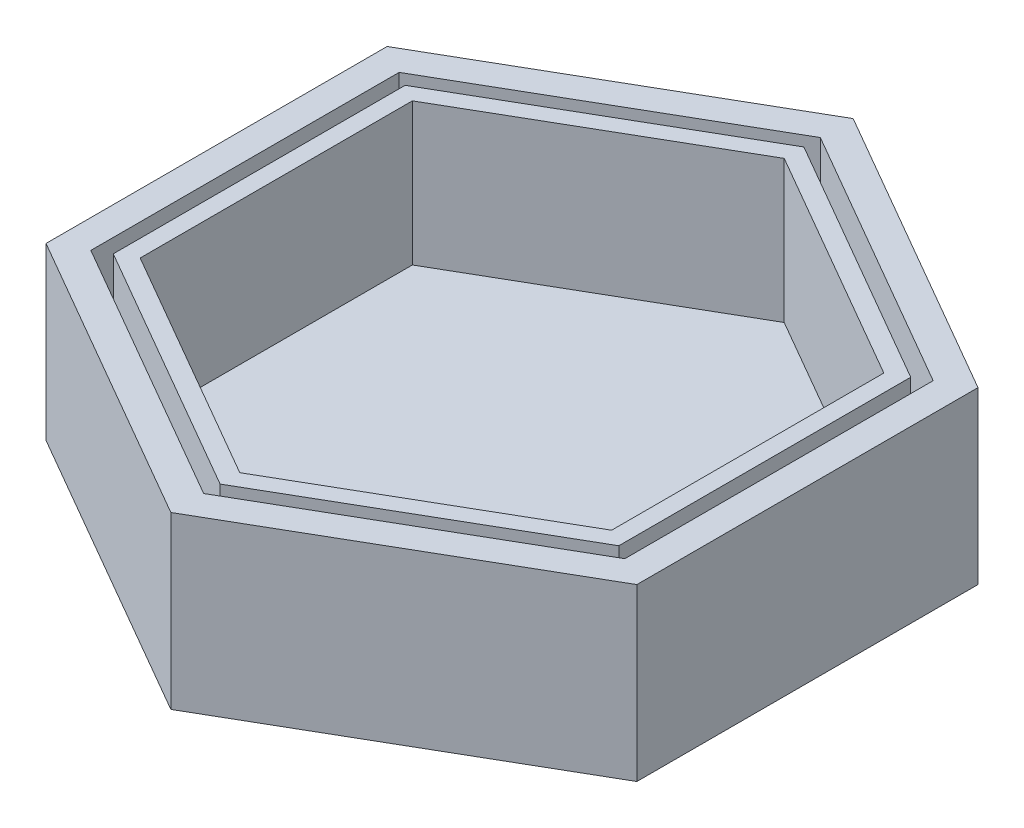
SolidWorks part; units mm, degrees
ref_plane "Front Plane" through (0, 0, 0) normal (0, 0, 1) x (1, 0, 0)
ref_plane "Top Plane" through (0, 0, 0) normal (0, 1, 0) x (1, 0, 0)
ref_plane "Right Plane" through (0, 0, 0) normal (1, 0, 0) x (0, 0, -1)
sketch "layout" plane through (0, 0, 0) normal (0, 1, 0) x (1, 0, 0)
  line L1 (0, -60) -> (51.9615, -30)
  line L2 (51.9615, -30) -> (51.9615, 30)
  line L3 (51.9615, 30) -> (0, 60)
  line L4 (0, 60) -> (-51.9615, 30)
  line L5 (-51.9615, 30) -> (-51.9615, -30)
  line L6 (-51.9615, -30) -> (0, -60)
  circle A0 centre (0, 0) radius 60 construction
  dimension "D1" = 120
extrude "Boss-Extrude1" add sketch "layout" along normal blind 5
sketch "Sketch2" plane through (0, 5, 0) normal (0, 1, 0) x (1, 0, 0)
  line L0 (-46.9615, -27.1132) -> (0, -54.2265)
  line L1 (0, -54.2265) -> (46.9615, -27.1132)
  line L2 (46.9615, -27.1132) -> (46.9615, 27.1132)
  line L3 (46.9615, 27.1132) -> (0, 54.2265)
  line L4 (0, 54.2265) -> (-46.9615, 27.1132)
  line L5 (-46.9615, 27.1132) -> (-46.9615, -27.1132)
  line L6 (-51.9615, -30) -> (0, -60)
  line L7 (0, -60) -> (51.9615, -30)
  line L8 (51.9615, -30) -> (51.9615, 30)
  line L9 (51.9615, 30) -> (0, 60)
  line L10 (0, 60) -> (-51.9615, 30)
  line L11 (-51.9615, 30) -> (-51.9615, -30)
  line L12 (-51.9615, -30) -> (0, -60)
  line L13 (0, -60) -> (51.9615, -30)
  line L14 (51.9615, -30) -> (51.9615, 30)
  line L15 (51.9615, 30) -> (0, 60)
  line L16 (0, 60) -> (-51.9615, 30)
  line L17 (-51.9615, 30) -> (-51.9615, -30)
  dimension "D1" = 0
  dimension "D2" = 5
extrude "Boss-Extrude2" add sketch "Sketch2" along normal blind 25
sketch "Sketch3" plane through (0, 5, 0) normal (0, 1, 0) x (1, 0, 0)
  line L0 (-44.4615, 25.6699) -> (-44.4615, -25.6699)
  line L1 (-44.4615, -25.6699) -> (0, -51.3397)
  line L2 (0, -51.3397) -> (44.4615, -25.6699)
  line L3 (44.4615, -25.6699) -> (44.4615, 25.6699)
  line L4 (44.4615, 25.6699) -> (0, 51.3397)
  line L5 (0, 51.3397) -> (-44.4615, 25.6699)
  line L6 (-46.9615, 27.1132) -> (-46.9615, -27.1132)
  line L7 (-46.9615, -27.1132) -> (0, -54.2265)
  line L8 (0, -54.2265) -> (46.9615, -27.1132)
  line L9 (46.9615, -27.1132) -> (46.9615, 27.1132)
  line L10 (46.9615, 27.1132) -> (0, 54.2265)
  line L11 (0, 54.2265) -> (-46.9615, 27.1132)
  line L12 (-46.9615, 27.1132) -> (-46.9615, -27.1132) construction
  line L13 (-46.9615, -27.1132) -> (0, -54.2265) construction
  line L14 (0, -54.2265) -> (46.9615, -27.1132) construction
  line L15 (46.9615, -27.1132) -> (46.9615, 27.1132) construction
  line L16 (46.9615, 27.1132) -> (0, 54.2265) construction
  line L17 (0, 54.2265) -> (-46.9615, 27.1132) construction
  line L18 (0, 47.8756) -> (-41.4615, 23.9378)
  line L19 (-41.4615, 23.9378) -> (-41.4615, -23.9378)
  line L20 (-41.4615, -23.9378) -> (0, -47.8756)
  line L21 (0, -47.8756) -> (41.4615, -23.9378)
  line L22 (41.4615, -23.9378) -> (41.4615, 23.9378)
  line L23 (41.4615, 23.9378) -> (0, 47.8756)
  dimension "D1" = 0
  dimension "D2" = 2.5
  dimension "D3" = 3
extrude "Boss-Extrude4" add sketch "Sketch3" along normal blind 25
sketch "Sketch4" plane through (41.4615, 0, 0) normal (-1, 0, 0) x (0, 0, 1)
  line L0 (0, 5) -> (0, 10) construction
  line L1 (-5, 5) -> (5, 5)
  line L2 (-5, 5) -> (0, 10)
  line L3 (0, 10) -> (5, 5)
  line L4 (-23.9378, 5) -> (23.9378, 5)
  line L5 (23.9378, 5) -> (23.9378, 30)
  line L6 (23.9378, 30) -> (-23.9378, 30)
  line L7 (-23.9378, 30) -> (-23.9378, 5)
  line L8 (-23.9378, 5) -> (23.9378, 5) construction
  line L9 (23.9378, 5) -> (23.9378, 30) construction
  line L10 (23.9378, 30) -> (-23.9378, 30) construction
  line L11 (-23.9378, 30) -> (-23.9378, 5) construction
  dimension "D2" = 10
  dimension "D3" = 5
  dimension "D1" = 0
extrude "Cut-Extrude1" cut sketch "Sketch4" against normal up to surface (3 mm away) up to face at (44.4615, 17.5, 0)
sketch "Sketch7" plane through (0, 0, 0) normal (0, 0, 1) x (1, 0, 0)
  line L1 (18.3981, -19.8787) -> (34.1859, 27.5634)
  line L2 (34.1859, 27.5634) -> (0.9938, 64.957)
  line L3 (0.9938, 64.957) -> (-47.9861, 54.9086)
  line L4 (-47.9861, 54.9086) -> (-63.7739, 7.4666)
  line L5 (-63.7739, 7.4666) -> (-30.5818, -29.927)
  line L6 (-30.5818, -29.927) -> (18.3981, -19.8787)
  circle A0 centre (-14.794, 17.515) radius 50 construction
  dimension "D1" = 100
